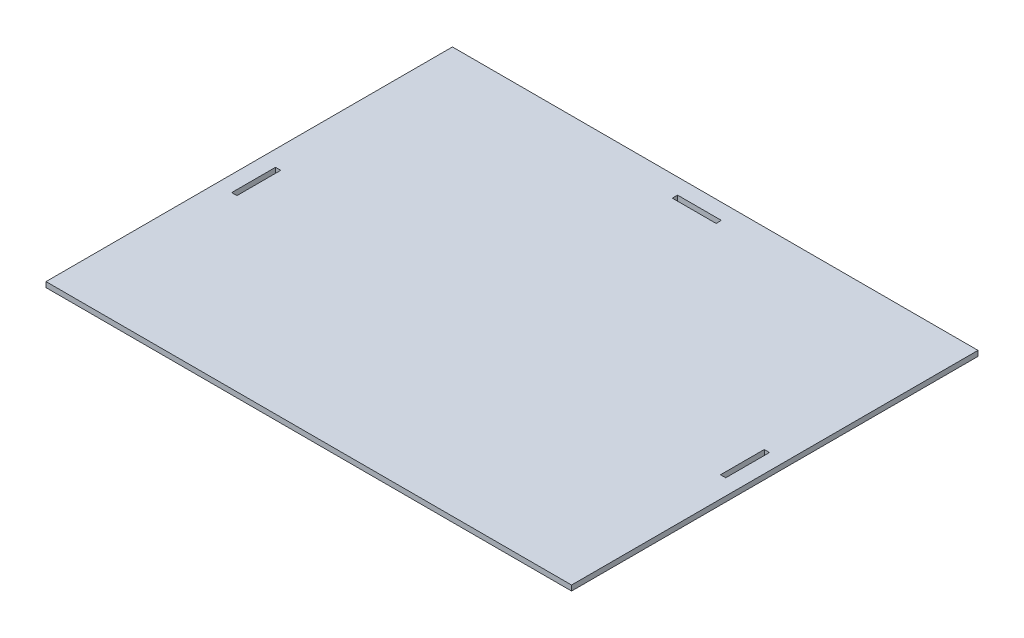
SolidWorks part; units mm, degrees
material "Maple"
ref_plane "Front Plane" through (0, 0, 0) normal (0, 0, 1) x (1, 0, 0)
ref_plane "Top Plane" through (0, 0, 0) normal (0, 1, 0) x (1, 0, 0)
ref_plane "Right Plane" through (0, 0, 0) normal (1, 0, 0) x (0, 0, -1)
sketch "Sketch1" plane through (0, 0, 0) normal (0, 1, 0) x (1, 0, 0)
  line L0 (300, 0) -> (300, -491) construction
  line L1 (0, 0) -> (600, 0)
  line L2 (0, 0) -> (0, -464)
  line L3 (0, -464) -> (257, -464)
  line L4 (600, 0) -> (600, -464)
  line L6 (307, -464) -> (600, -464)
  line L7 (275, -18) -> (325, -18)
  line L8 (275, -18) -> (275, -24)
  line L9 (275, -24) -> (325, -24)
  line L10 (325, -18) -> (325, -24)
  line L11 (275, -18) -> (325, -24) construction
  line L12 (275, -24) -> (325, -18) construction
  line L17 (582, -270) -> (576, -270)
  line L18 (18, -220) -> (24, -220)
  line L19 (18, -220) -> (18, -270)
  line L20 (18, -270) -> (24, -270)
  line L21 (24, -220) -> (24, -270)
  line L22 (18, -220) -> (24, -270) construction
  line L23 (18, -270) -> (24, -220) construction
  line L24 (576, -220) -> (576, -270)
  line L25 (582, -220) -> (576, -220)
  line L26 (582, -220) -> (582, -270)
  line L27 (307, -464) -> (257, -464)
  point P6 (21, -245)
  point P9 (300, -21)
  dimension "D1" = 600
  dimension "D2" = 464
  dimension "D3" = 50
  dimension "D4" = 6
  dimension "D5" = 18
  dimension "D6" = 196
  dimension "D7" = 6
  dimension "D8" = 50
  dimension "D9" = 18
extrude "Boss-Extrude1" add sketch "Sketch1" along normal blind 6
